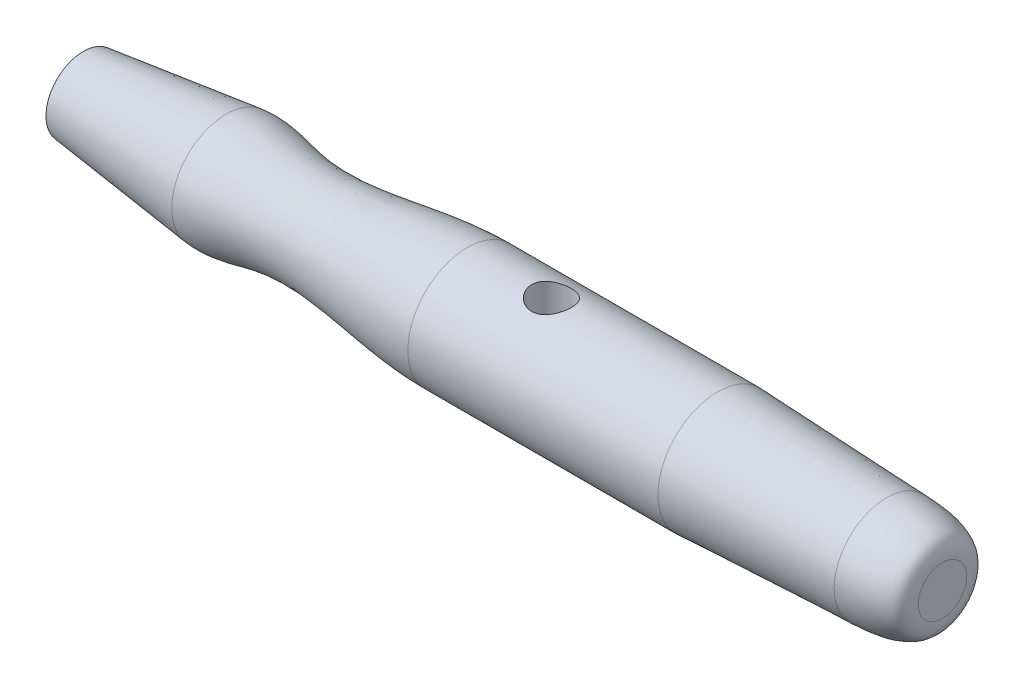
SolidWorks part; units mm, degrees
ref_plane "Front Plane" through (0, 0, 0) normal (0, 0, 1) x (1, 0, 0)
ref_plane "Top Plane" through (0, 0, 0) normal (0, 1, 0) x (1, 0, 0)
ref_plane "Right Plane" through (0, 0, 0) normal (1, 0, 0) x (0, 0, -1)
sketch "Sketch1" plane through (0, 0, 0) normal (0, 0, 1) x (1, 0, 0)
  line L0 (-137.5, 0) -> (137.5, 0)
  line L1 (-137.5, 11.938) -> (-137.5, 0)
  line L2 (-91.78, 17.399) -> (-91.78, 0) construction
  line L3 (-72.984, 15.24) -> (-72.984, 0) construction
  line L4 (-14.564, 19.05) -> (-14.564, 0) construction
  line L5 (-137.5, 11.938) -> (-91.78, 17.399)
  line L6 (119.602, 0) -> (119.602, 16.764) construction
  line L7 (65.5, 0) -> (65.5, 19.05) construction
  line L8 (65.5, 19.05) -> (119.602, 16.764)
  line L9 (-14.564, 19.05) -> (65.5, 19.05)
  line L10 (133.826, 14.351) -> (133.826, 0) construction
  line L11 (137.5, 0) -> (137.5, 7.747) construction
  line L12 (137.5, 7.747) -> (137.5, 0)
  spline S0 degree 3 poles (-91.78, 17.399) (-84.9013, 18.2206) (-60.5493, 10.0128) (-35.8294, 19.05) (-14.564, 19.05) knots 0 0 0 0 0.244238 1 1 1 1
  spline S1 degree 3 poles (119.602, 16.764) (126.4467, 16.4748) (132.2517, 15.7308) (137.5, 12.3228) (137.5, 7.747) knots 0 0 0 0 0.656248 1 1 1 1
  point P9 (0, 0)
  point P16 (0, 0)
  point P21 (0, 0)
  dimension "D2" = 45.72
  dimension "D3" = 11.938
  dimension "D1" = 16.764
  dimension "D4" = 64.516
  dimension "D5" = 15.24
  dimension "D6" = 19.05
  dimension "D7" = 122.936
  dimension "D8" = 203
  dimension "D9" = 19.05
  dimension "D10" = 54.102
  dimension "D11" = 275
  dimension "D12" = 14.351
  dimension "D13" = 7.747
  dimension "D14" = 14.224
  dimension "D15" = 17.399
revolve "Revolve1" add sketch "Sketch1" angle 360 about L0
sketch "Sketch3" plane through (0, 0, 0) normal (0, 1, 0) x (1, 0, 0)
  line L0 (-137.5, 11.938) -> (-137.5, -11.938) construction
  circle A0 centre (12.36, 0) radius 6.35
  point P4 (0, 0)
  dimension "D1" = 12.7
  dimension "D2" = 149.86
extrude "Cut-Extrude1" cut sketch "Sketch3" along normal up to next
